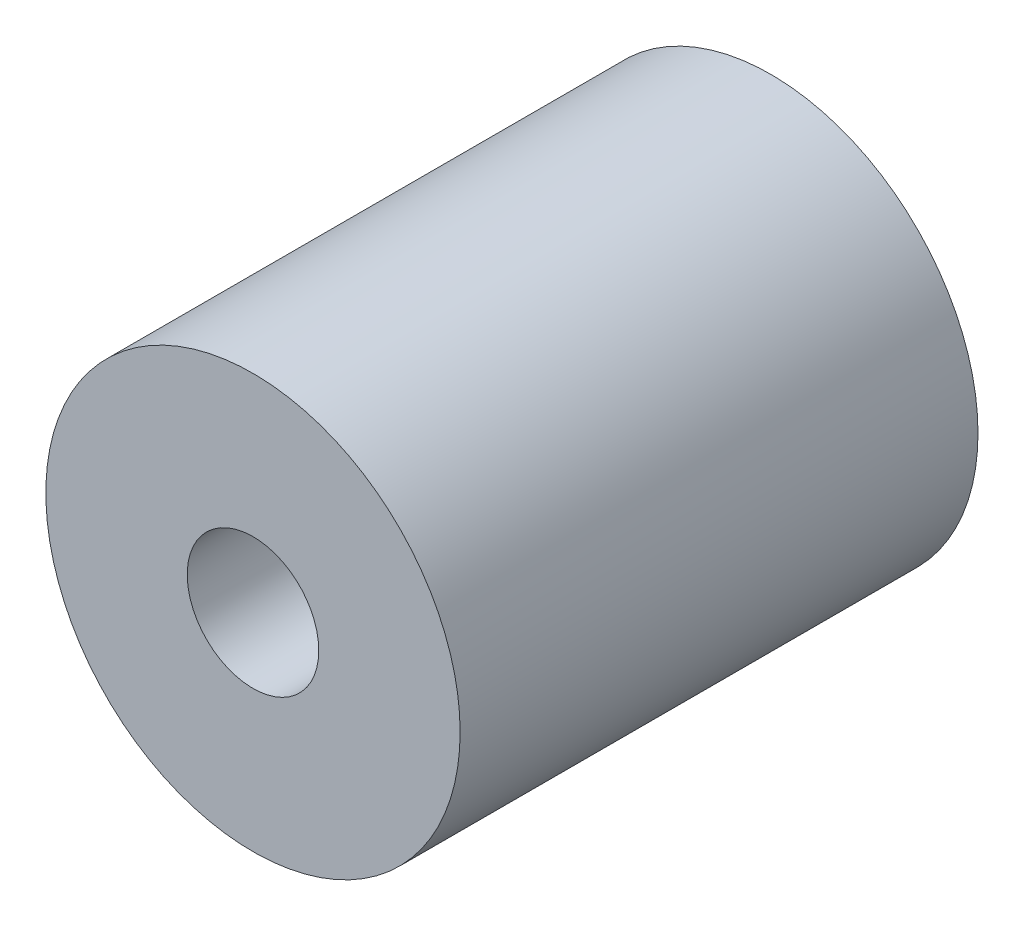
SolidWorks part; units mm, degrees
ref_plane "Front Plane" through (0, 0, 0) normal (0, 0, 1) x (1, 0, 0)
ref_plane "Top Plane" through (0, 0, 0) normal (0, 1, 0) x (1, 0, 0)
ref_plane "Right Plane" through (0, 0, 0) normal (1, 0, 0) x (0, 0, -1)
ref_plane "Plane1"
sketch "Sketch1" plane through (0, 0, 0) normal (0, 0, 1) x (1, 0, 0)
  circle A0 centre (0, 0) radius 10
  dimension "D1" = 20
extrude "Extrusion1" add sketch "Sketch1" along normal blind 25
sketch "Sketch2" plane through (0, 0, 25) normal (0, 0, 1) x (1, 0, 0)
  circle A0 centre (0, 0) radius 3.175
  dimension "D1" = 6.35
extrude "Extrusion2" cut sketch "Sketch2" against normal blind 12.5
sketch "Sketch3" plane through (0, 0, 0) normal (0, 0, -1) x (-1, 0, 0)
  circle A0 centre (0, 0) radius 5
  dimension "D1" = 10
extrude "Extrusion3" cut sketch "Sketch3" against normal blind 12.5
